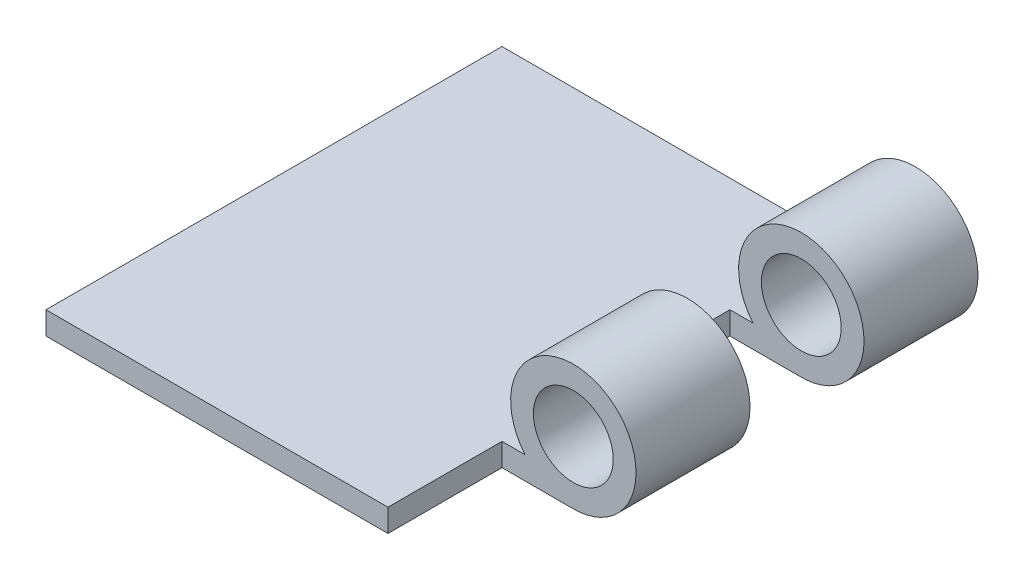
SolidWorks part; units mm, degrees
material "Nylon 6/10"
ref_plane "Front Plane" through (0, 0, 0) normal (0, 0, 1) x (1, 0, 0)
ref_plane "Top Plane" through (0, 0, 0) normal (0, 1, 0) x (1, 0, 0)
ref_plane "Right Plane" through (0, 0, 0) normal (1, 0, 0) x (0, 0, -1)
sketch "Sketch1" plane through (0, 0, 0) normal (0, 1, 0) x (1, 0, 0)
  line L0 (0, 10) -> (0, -10)
  line L1 (0, 10) -> (18, 10)
  line L3 (15, -10) -> (0, -10)
  line L4 (18, 16.4537) -> (18, 5) construction
  line L5 (18, 10) -> (18, 5)
  line L6 (18, 5) -> (15, 5)
  line L7 (15, 5) -> (15, 0)
  line L8 (15, 0) -> (18, 0)
  line L9 (18, 0) -> (18, -5)
  line L10 (18, -5) -> (15, -5)
  line L11 (15, -5) -> (15, -10)
  line L12 (18, 0) -> (18, -5) construction
  point P3 (0, 0)
  dimension "D2" = 20
  dimension "D3" = 5
  dimension "D4" = 3
  dimension "D5" = 3
  dimension "D6" = 5
extrude "Boss-Extrude1" add sketch "Sketch1" against normal blind 1 contours L0 L3 L11 L10 L9 L8 L7 L6 L5 L1
sketch "Sketch2" plane through (0, 0, -10) normal (0, 0, -1) x (-1, 0, 0)
  line L0 (0, -1) -> (-18, -1) construction
  circle A0 centre (-18.1302, 1.75) radius 2.75
  circle A1 centre (-18.1302, 1.75) radius 1.75
  dimension "D1" = 5.5
  dimension "D2" = 1
extrude "Boss-Extrude2" add sketch "Sketch2" against normal up to surface (5 mm away) up to face at (16.5, -0.5, -5)
sketch "Sketch3" plane through (0, 0, 0) normal (0, 0, -1) x (-1, 0, 0)
  line L0 (-15, -1) -> (-18, -1) construction
  circle A0 centre (-18.1302, 1.75) radius 2.75
  circle A1 centre (-18.1302, 1.75) radius 1.75
  dimension "D1" = 1
extrude "Boss-Extrude3" add sketch "Sketch3" against normal up to surface (5 mm away) up to face at (16.5, -0.5, 5)
